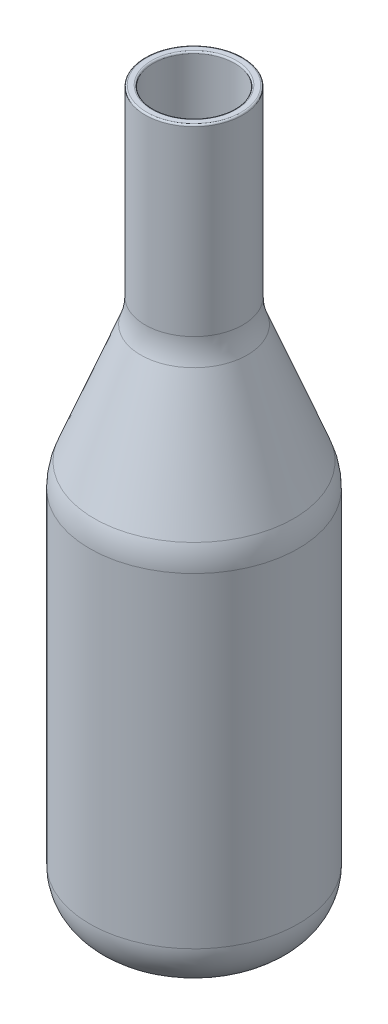
SolidWorks part; units mm, degrees
ref_plane "Front Plane" through (0, 0, 0) normal (0, 0, 1) x (1, 0, 0)
ref_plane "Top Plane" through (0, 0, 0) normal (0, 1, 0) x (1, 0, 0)
ref_plane "Right Plane" through (0, 0, 0) normal (1, 0, 0) x (0, 0, -1)
sketch "Sketch1" plane through (0, 0, 0) normal (1, 0, 0) x (0, 0, -1)
  line L0 (0, 0) -> (0, 93.6303) construction
  line L1 (0, 0) -> (17, 0)
  line L2 (32, 15) -> (32, 114.7513)
  line L3 (15, 221.5) -> (15, 165.7083)
  line L4 (16.3775, 158.4142) -> (30.6225, 122.0453)
  line L5 (0, 0) -> (0, 2.5)
  line L6 (0, 2.5) -> (14.5, 2.5)
  line L7 (14.5, 222) -> (13, 222)
  line L8 (29.5, 17.5) -> (29.5, 114.2791)
  line L9 (28.1225, 121.5732) -> (13.8775, 157.9421)
  line L10 (12.5, 165.2361) -> (12.5, 211.6334)
  line L11 (12.5, 211.6334) -> (12.5, 221.5)
  arc A0 (15, 221.5) -> (14.5, 222) centre (14.5, 221.5) ccw
  arc A1 (16.3775, 158.4142) -> (15, 165.7083) centre (35, 165.7083) cw
  arc A2 (30.6225, 122.0453) -> (32, 114.7513) centre (12, 114.7513) cw
  arc A3 (29.5, 114.2791) -> (28.1225, 121.5732) centre (9.5, 114.2791) ccw
  arc A4 (32, 15) -> (17, 0) centre (17, 15) cw
  arc A5 (13.8775, 157.9421) -> (12.5, 165.2361) centre (32.5, 165.2361) cw
  arc A6 (12.5, 221.5) -> (13, 222) centre (13, 221.5) cw
  arc A7 (14.5, 2.5) -> (29.5, 17.5) centre (14.5, 17.5) ccw
  point P8 (15, 222)
  point P20 (0, 46.8152)
  point P28 (0, 0)
  point P30 (15, 193.6041)
  point P31 (29.5, 2.5)
  dimension "D2" = 0.5
  dimension "D3" = 0.5
  dimension "D4" = 20
  dimension "D5" = 20
  dimension "D6" = 15
  dimension "D12" = 20
  dimension "D13" = 20
  dimension "D15" = 15
  dimension "D1" = 222
  dimension "D7" = 32
  dimension "D8" = 2.5
  dimension "D9" = 2.5
  dimension "D10" = 2.5
  dimension "D11" = 2.5
  dimension "D14" = 15
revolve "Revolve1" add sketch "Sketch1" angle 360 about L0
